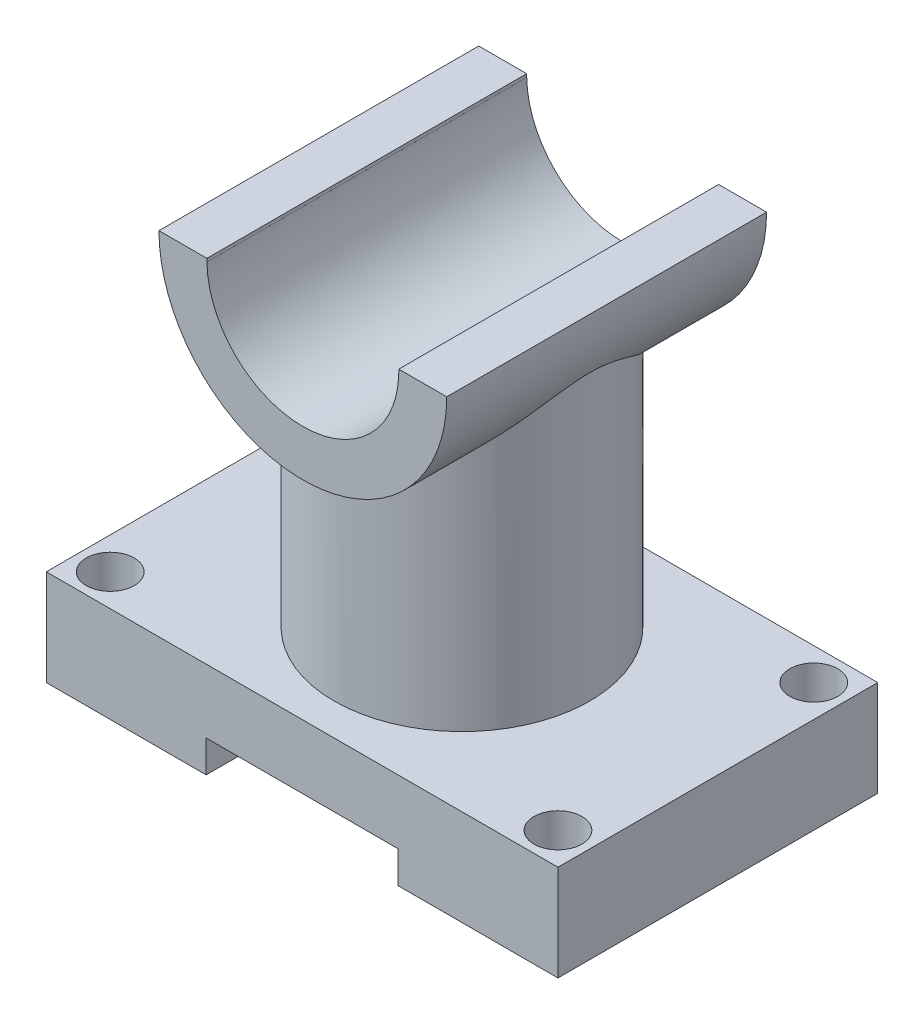
SolidWorks part; units mm, degrees
ref_plane "Front Plane" through (0, 0, 0) normal (0, 0, 1) x (1, 0, 0)
ref_plane "Top Plane" through (0, 0, 0) normal (0, 1, 0) x (1, 0, 0)
ref_plane "Right Plane" through (0, 0, 0) normal (1, 0, 0) x (0, 0, -1)
sketch "Sketch1" plane through (0, 0, 0) normal (0, 1, 0) x (1, 0, 0)
  line L0 (-72.8546, 0) -> (87.1454, 0)
  line L1 (87.1454, 0) -> (87.1454, 100)
  line L2 (87.1454, 100) -> (-72.8546, 100)
  line L3 (-72.8546, 100) -> (-72.8546, 0)
  dimension "D1" = 160
  dimension "D2" = 100
extrude "Boss-Extrude1" add sketch "Sketch1" against normal blind 30
sketch "Sketch2" plane through (0, 0, 0) normal (0, 1, 0) x (1, 0, 0)
  line L0 (-72.8546, 0) -> (87.1454, 0) construction
  circle A0 centre (7.1454, 50) radius 40
  point P4 (7.1454, 0)
extrude "Boss-Extrude2" add sketch "Sketch2" along normal blind 110
sketch "Sketch3" plane through (0, 0, 0) normal (0, 0, 1) x (1, 0, 0)
  line L0 (-22.6204, 109.4662) -> (37.3796, 109.4662)
  line L2 (-37.6204, 110) -> (52.3796, 110)
  line L3 (47.1454, 110) -> (-32.8546, 110) construction
  arc A0 (-22.6204, 109.4662) -> (37.3796, 109.4662) centre (7.3796, 109.4662) ccw
  arc A2 (-37.6204, 110) -> (52.3796, 110) centre (7.3796, 110) ccw
  dimension "D1" = 30
  dimension "D2" = 45
extrude "Boss-Extrude3" add sketch "Sketch3" against normal blind 100
sketch "Sketch4" plane through (0, 0, 0) normal (0, 0, 1) x (1, 0, 0)
  line L0 (-22.6204, 109.4662) -> (37.3796, 109.4662)
  line L1 (37.3796, 109.4662) -> (-22.6204, 109.4662) construction
  arc A0 (-22.6204, 109.4662) -> (37.3796, 109.4662) centre (7.3796, 109.4662) ccw construction
  arc A1 (-22.6204, 109.4662) -> (37.3796, 109.4662) centre (7.3796, 109.4662) ccw construction
  arc A2 (-22.6204, 109.4662) -> (37.3796, 109.4662) centre (7.3796, 109.4662) ccw
extrude "Cut-Extrude1" cut sketch "Sketch4" against normal blind 100
sketch "Sketch6" plane through (0, 110, 0) normal (0, 1, 0) x (1, 0, 0)
  line L0 (-22.6204, 0) -> (-22.6204, 100)
  line L1 (-22.6204, 100) -> (-37.6204, 100)
  line L2 (-37.6204, 100) -> (-37.6204, 0)
  line L3 (-37.6204, 0) -> (-22.6204, 0)
  line L4 (37.3796, 0) -> (37.3796, 100)
  line L5 (37.3796, 100) -> (52.3796, 100)
  line L6 (52.3796, 100) -> (52.3796, 0)
  line L7 (-72.8546, 0) -> (87.1454, 0) construction
  line L8 (52.3796, 100) -> (52.3796, 0) construction
  line L9 (52.3796, 0) -> (37.3796, 0)
  line L10 (-22.6204, 0) -> (37.3796, 0)
  line L11 (-22.6204, 100) -> (37.3796, 100)
  line M9 (-37.6204, 0) -> (52.3796, 0)
  line M11 (52.3796, 100) -> (-37.6204, 100)
extrude "Cut-Extrude2" cut sketch "Sketch6" against normal blind 1 contours L4 L0 M9 M11
sketch "Sketch7" plane through (0, 0, 0) normal (0, 0, 1) x (1, 0, 0)
  line L0 (-22.8546, -30) -> (-22.8546, -20)
  line L1 (-72.8546, -30) -> (87.1454, -30) construction
  line L2 (-22.8546, -20) -> (37.1454, -20)
  line L3 (37.1454, -20) -> (37.1454, -30)
  line L4 (37.1454, -30) -> (-22.8546, -30)
  line L5 (-72.8546, 0) -> (87.1454, 0)
  point P10 (7.1454, 0)
  point P11 (7.1454, -20)
  line M7 (-72.8546, -30) -> (87.1454, -30)
  dimension "D1" = 10
  dimension "D2" = 60
extrude "Cut-Extrude3" cut sketch "Sketch7" against normal blind 100 contours L3 L2 L0 M7
sketch "Sketch8" plane through (0, 0, 0) normal (0, 1, 0) x (1, 0, 0)
  line L0 (87.1454, 0) -> (87.1454, 100) construction
  line L1 (-72.8546, 0) -> (87.1454, 0) construction
  line L2 (87.1454, 100) -> (-72.8546, 100) construction
  line L3 (-72.8546, 100) -> (-72.8546, 0) construction
  circle A0 centre (77.1454, 90) radius 7.5
  circle A1 centre (-62.8546, 90) radius 7.5
  circle A2 centre (-62.8546, 10) radius 7.5
  circle A3 centre (77.1454, 10) radius 7.5
  dimension "D1" = 10
  dimension "D2" = 10
  dimension "D3" = 10
  dimension "D4" = 10
  dimension "D5" = 10
  dimension "D6" = 10
  dimension "D7" = 10
  dimension "D8" = 10
extrude "Cut-Extrude4" cut sketch "Sketch8" against normal blind 100
